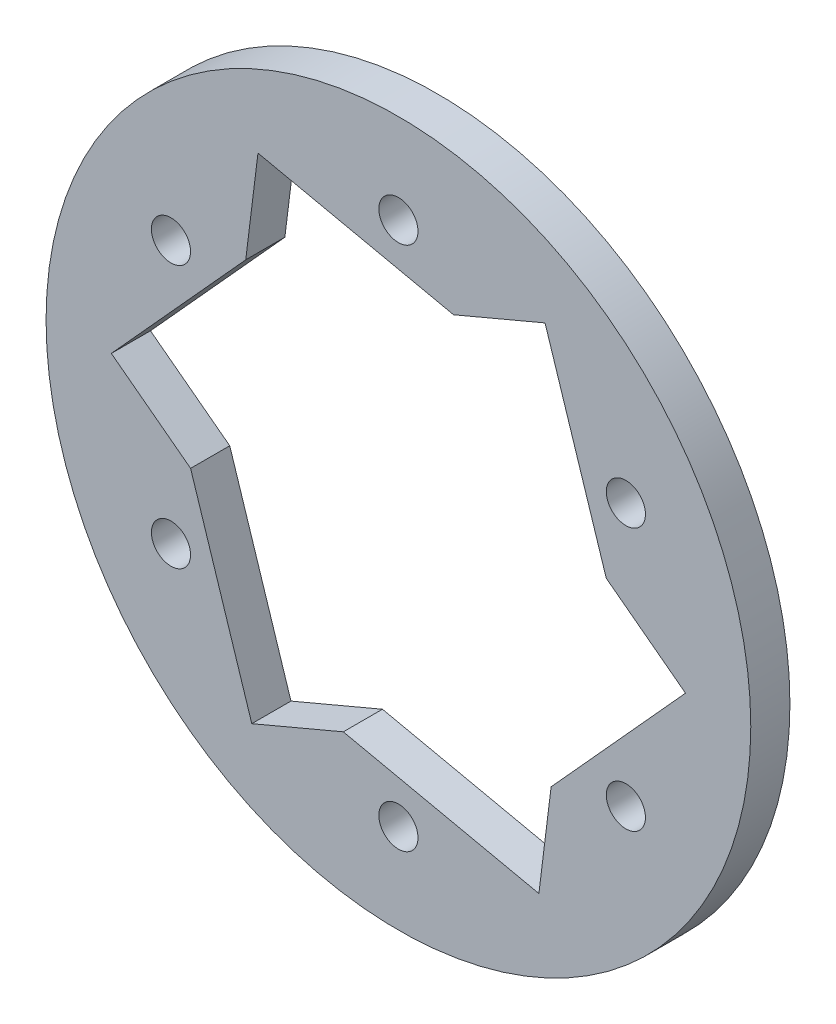
SolidWorks part; units mm, degrees
ref_plane "Alzado" through (0, 0, 0) normal (0, 0, 1) x (1, 0, 0)
ref_plane "Planta" through (0, 0, 0) normal (0, 1, 0) x (1, 0, 0)
ref_plane "Vista lateral" through (0, 0, 0) normal (1, 0, 0) x (0, 0, -1)
sketch "Model" plane through (0, 0, 0) normal (0, 0, 1) x (1, 0, 0)
  line L0 (174.3527, 246.2684) -> (180.4256, 241.6792)
  line L1 (170.1281, 230.3184) -> (169.1902, 222.7645)
  line L2 (154.2027, 226.002) -> (147.1919, 223.0373)
  line L3 (142.5019, 237.6356) -> (136.4273, 242.2261)
  line L4 (146.7265, 253.5856) -> (147.6644, 261.1395)
  line L5 (162.6519, 257.902) -> (169.6627, 260.8667)
  line L6 (162.6519, 257.902) -> (147.6644, 261.1395)
  line L7 (146.7265, 253.5856) -> (136.4273, 242.2261)
  line L8 (142.5019, 237.6356) -> (147.1919, 223.0373)
  line L9 (154.2027, 226.002) -> (169.1902, 222.7645)
  line L10 (170.1281, 230.3184) -> (180.4256, 241.6792)
  line L11 (174.3527, 246.2684) -> (169.6627, 260.8667)
  circle A0 centre (158.4273, 262.0766) radius 1.5
  circle A1 centre (140.9989, 252.0143) radius 1.5
  circle A2 centre (140.9989, 231.8897) radius 1.5
  circle A3 centre (158.4273, 221.8274) radius 1.5
  circle A4 centre (175.8557, 231.8897) radius 1.5
  circle A5 centre (158.4273, 241.952) radius 27
  circle A6 centre (175.8557, 252.0143) radius 1.5
extrude "Saliente-Extruir1" add sketch "Model" along normal blind 3
